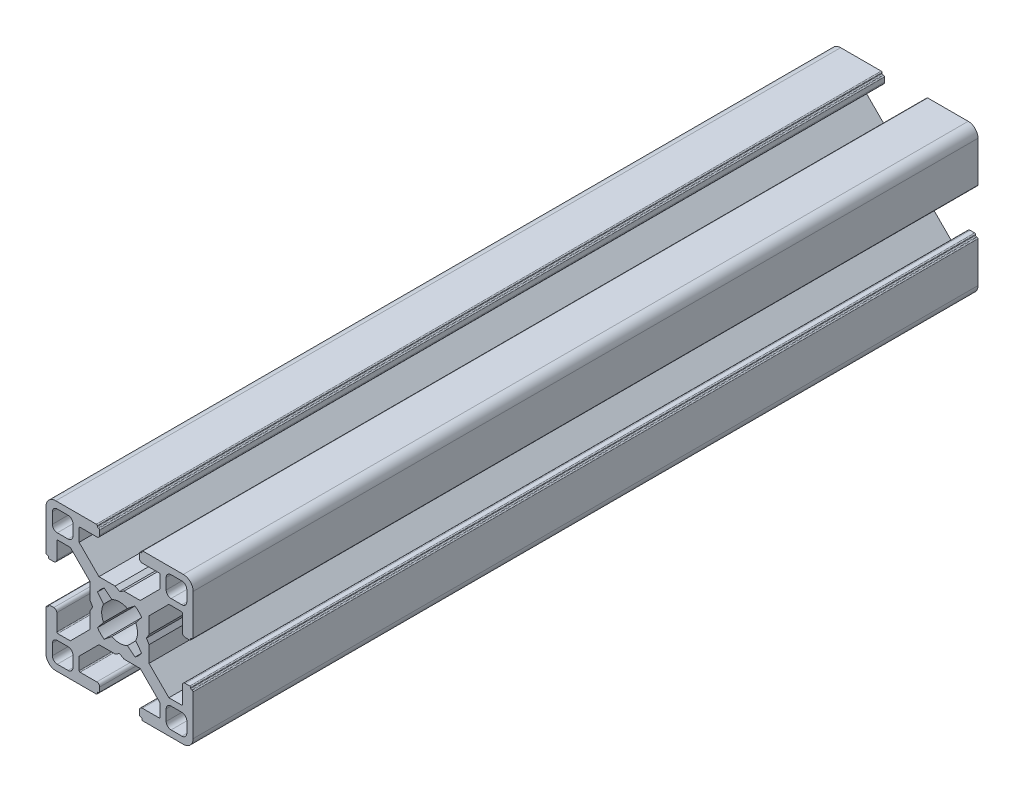
SolidWorks part; units mm, degrees
material "6061 Alloy"
ref_plane "Front" through (0, 0, 0) normal (0, 0, 1) x (1, 0, 0)
ref_plane "Top" through (0, 0, 0) normal (0, 1, 0) x (1, 0, 0)
ref_plane "Right" through (0, 0, 0) normal (1, 0, 0) x (0, 0, -1)
sketch "Sketch1" plane through (0, 0, 0) normal (0, 0, 1) x (1, 0, 0)
  line L0 (13.7, 12.7) -> (13.7, 10.5)
  line L1 (10.5, 9.5) -> (12.7, 9.5)
  line L2 (9.5, 12.7) -> (9.5, 10.5)
  line L3 (10.5, 13.7) -> (12.7, 13.7)
  line L4 (3.1359, 4.5184) -> (1.6001, 3.2806)
  line L5 (3.2806, 1.6001) -> (4.5053, 3.1547)
  line L6 (6.0045, 0.9) -> (5.4849, 0)
  line L7 (6.0045, 4.2045) -> (6.0045, 0.9)
  line L8 (0, -5.4849) -> (0.9, -6)
  line L9 (0.9, -6) -> (4.2045, -6)
  line L10 (4.2045, -6) -> (8.25, -10.05)
  line L11 (8.25, -10.05) -> (8.25, -12.6)
  line L12 (4.65, -12.8) -> (8.05, -12.8)
  line L13 (4.05, -14.3) -> (4.05, -13.4)
  line L14 (4.25, -14.5) -> (4.35, -14.5)
  line L15 (4.55, -14.8) -> (4.55, -14.7)
  line L16 (4.75, -15) -> (13, -15)
  line L17 (15, -13) -> (15, -4.75)
  line L18 (14.7, -4.55) -> (14.8, -4.55)
  line L19 (14.5, -4.35) -> (14.5, -4.25)
  line L20 (13.4, -4.05) -> (14.3, -4.05)
  line L21 (12.8, -8.05) -> (12.8, -4.65)
  line L22 (12.6, -8.25) -> (10.05, -8.25)
  line L23 (10.05, -8.25) -> (6.0045, -4.2045)
  line L24 (6.0045, -4.2045) -> (6.0045, -0.9)
  line L25 (6.0045, -0.9) -> (5.4849, 0)
  line L26 (10.05, 8.25) -> (6.0045, 4.2045)
  line L27 (12.6, 8.25) -> (10.05, 8.25)
  line L28 (12.8, 8.05) -> (12.8, 4.65)
  line L29 (13.4, 4.05) -> (14.3, 4.05)
  line L30 (14.5, 4.35) -> (14.5, 4.25)
  line L31 (14.7, 4.55) -> (14.8, 4.55)
  line L32 (15, 13) -> (15, 4.75)
  line L33 (4.75, 15) -> (13, 15)
  line L34 (4.55, 14.8) -> (4.55, 14.7)
  line L35 (4.25, 14.5) -> (4.35, 14.5)
  line L36 (4.05, 14.3) -> (4.05, 13.4)
  line L37 (4.65, 12.8) -> (8.05, 12.8)
  line L38 (8.25, 10.05) -> (8.25, 12.6)
  line L39 (4.2045, 6) -> (8.25, 10.05)
  line L40 (0.9, 6) -> (4.2045, 6)
  line L41 (0, 5.4849) -> (0.9, 6)
  line L42 (-13.7, -12.7) -> (-13.7, -10.5)
  line L43 (-10.5, -9.5) -> (-12.7, -9.5)
  line L44 (-9.5, -12.7) -> (-9.5, -10.5)
  line L45 (-10.5, -13.7) -> (-12.7, -13.7)
  line L46 (-3.1359, -4.5184) -> (-1.6001, -3.2806)
  line L47 (-3.2806, -1.6001) -> (-4.5053, -3.1547)
  line L48 (0, 5.4849) -> (-0.9, 6)
  line L49 (-0.9, 6) -> (-4.2045, 6)
  line L50 (-4.2045, 6) -> (-8.25, 10.05)
  line L51 (-8.25, 10.05) -> (-8.25, 12.6)
  line L52 (-4.65, 12.8) -> (-8.05, 12.8)
  line L53 (-4.05, 14.3) -> (-4.05, 13.4)
  line L54 (-4.25, 14.5) -> (-4.35, 14.5)
  line L55 (-4.55, 14.8) -> (-4.55, 14.7)
  line L56 (-4.75, 15) -> (-13, 15)
  line L57 (-15, 13) -> (-15, 4.75)
  line L58 (-14.7, 4.55) -> (-14.8, 4.55)
  line L59 (-14.5, 4.35) -> (-14.5, 4.25)
  line L60 (-13.4, 4.05) -> (-14.3, 4.05)
  line L61 (-12.8, 8.05) -> (-12.8, 4.65)
  line L62 (-12.6, 8.25) -> (-10.05, 8.25)
  line L63 (-10.05, 8.25) -> (-6.0045, 4.2045)
  line L64 (-6.0045, -0.9) -> (-5.4849, 0)
  line L65 (-6.0045, -4.2045) -> (-6.0045, -0.9)
  line L66 (-10.05, -8.25) -> (-6.0045, -4.2045)
  line L67 (-12.6, -8.25) -> (-10.05, -8.25)
  line L68 (-12.8, -8.05) -> (-12.8, -4.65)
  line L69 (-13.4, -4.05) -> (-14.3, -4.05)
  line L70 (-14.5, -4.35) -> (-14.5, -4.25)
  line L71 (-14.7, -4.55) -> (-14.8, -4.55)
  line L72 (-15, -13) -> (-15, -4.75)
  line L73 (-4.75, -15) -> (-13, -15)
  line L74 (-4.55, -14.8) -> (-4.55, -14.7)
  line L75 (-4.25, -14.5) -> (-4.35, -14.5)
  line L76 (-4.05, -14.3) -> (-4.05, -13.4)
  line L77 (3.2806, -1.6001) -> (4.5053, -3.1547)
  line L78 (3.1359, -4.5184) -> (1.6001, -3.2806)
  line L79 (-4.65, -12.8) -> (-8.05, -12.8)
  line L80 (-8.25, -10.05) -> (-8.25, -12.6)
  line L81 (-4.2045, -6) -> (-8.25, -10.05)
  line L82 (-0.9, -6) -> (-4.2045, -6)
  line L83 (0, -5.4849) -> (-0.9, -6)
  line L84 (10.5, -13.7) -> (12.7, -13.7)
  line L85 (9.5, -12.7) -> (9.5, -10.5)
  line L86 (10.5, -9.5) -> (12.7, -9.5)
  line L87 (13.7, -12.7) -> (13.7, -10.5)
  line L88 (-6.0045, 4.2045) -> (-6.0045, 0.9)
  line L89 (-6.0045, 0.9) -> (-5.4849, 0)
  line L90 (-3.2806, 1.6001) -> (-4.5053, 3.1547)
  line L91 (-3.1359, 4.5184) -> (-1.6001, 3.2806)
  line L92 (-10.5, 13.7) -> (-12.7, 13.7)
  line L93 (-9.5, 12.7) -> (-9.5, 10.5)
  line L94 (-10.5, 9.5) -> (-12.7, 9.5)
  line L95 (-13.7, 12.7) -> (-13.7, 10.5)
  line L96 (-23.4857, 0) -> (20.9308, 0) construction
  line L97 (0, 17.9563) -> (0, -17.361) construction
  arc A0 (13.7, 12.7) -> (12.7, 13.7) centre (12.7, 12.7) ccw
  arc A1 (12.7, 9.5) -> (13.7, 10.5) centre (12.7, 10.5) ccw
  arc A2 (9.5, 10.5) -> (10.5, 9.5) centre (10.5, 10.5) ccw
  arc A3 (10.5, 13.7) -> (9.5, 12.7) centre (10.5, 12.7) ccw
  arc A4 (1.6001, 3.2806) -> (-1.6001, 3.2806) centre (0, 0) ccw
  arc A5 (8.25, -12.6) -> (8.05, -12.8) centre (8.05, -12.6) cw
  arc A6 (4.65, -12.8) -> (4.05, -13.4) centre (4.65, -13.4) ccw
  arc A7 (4.05, -14.3) -> (4.25, -14.5) centre (4.25, -14.3) ccw
  arc A8 (4.35, -14.5) -> (4.55, -14.7) centre (4.35, -14.7) cw
  arc A9 (4.55, -14.8) -> (4.75, -15) centre (4.75, -14.8) ccw
  arc A10 (13, -15) -> (15, -13) centre (13, -13) ccw
  arc A11 (15, -4.75) -> (14.8, -4.55) centre (14.8, -4.75) ccw
  arc A12 (14.7, -4.55) -> (14.5, -4.35) centre (14.7, -4.35) cw
  arc A13 (14.5, -4.25) -> (14.3, -4.05) centre (14.3, -4.25) ccw
  arc A14 (13.4, -4.05) -> (12.8, -4.65) centre (13.4, -4.65) ccw
  arc A15 (12.8, -8.05) -> (12.6, -8.25) centre (12.6, -8.05) cw
  arc A16 (4.5053, 3.1547) -> (3.1359, 4.5184) centre (0, 0) ccw
  arc A17 (12.8, 8.05) -> (12.6, 8.25) centre (12.6, 8.05) ccw
  arc A18 (13.4, 4.05) -> (12.8, 4.65) centre (13.4, 4.65) cw
  arc A19 (14.5, 4.25) -> (14.3, 4.05) centre (14.3, 4.25) cw
  arc A20 (14.7, 4.55) -> (14.5, 4.35) centre (14.7, 4.35) ccw
  arc A21 (15, 4.75) -> (14.8, 4.55) centre (14.8, 4.75) cw
  arc A22 (13, 15) -> (15, 13) centre (13, 13) cw
  arc A23 (4.55, 14.8) -> (4.75, 15) centre (4.75, 14.8) cw
  arc A24 (4.35, 14.5) -> (4.55, 14.7) centre (4.35, 14.7) ccw
  arc A25 (4.05, 14.3) -> (4.25, 14.5) centre (4.25, 14.3) cw
  arc A26 (4.65, 12.8) -> (4.05, 13.4) centre (4.65, 13.4) cw
  arc A27 (8.25, 12.6) -> (8.05, 12.8) centre (8.05, 12.6) ccw
  arc A28 (-13.7, -12.7) -> (-12.7, -13.7) centre (-12.7, -12.7) ccw
  arc A29 (-12.7, -9.5) -> (-13.7, -10.5) centre (-12.7, -10.5) ccw
  arc A30 (-9.5, -10.5) -> (-10.5, -9.5) centre (-10.5, -10.5) ccw
  arc A31 (-10.5, -13.7) -> (-9.5, -12.7) centre (-10.5, -12.7) ccw
  arc A32 (-4.5053, -3.1547) -> (-3.1359, -4.5184) centre (0, 0) ccw
  arc A33 (-3.2806, 1.6001) -> (-3.2806, -1.6001) centre (0, 0) ccw
  arc A34 (-8.25, 12.6) -> (-8.05, 12.8) centre (-8.05, 12.6) cw
  arc A35 (-4.65, 12.8) -> (-4.05, 13.4) centre (-4.65, 13.4) ccw
  arc A36 (-4.05, 14.3) -> (-4.25, 14.5) centre (-4.25, 14.3) ccw
  arc A37 (-4.35, 14.5) -> (-4.55, 14.7) centre (-4.35, 14.7) cw
  arc A38 (-4.55, 14.8) -> (-4.75, 15) centre (-4.75, 14.8) ccw
  arc A39 (-13, 15) -> (-15, 13) centre (-13, 13) ccw
  arc A40 (-15, 4.75) -> (-14.8, 4.55) centre (-14.8, 4.75) ccw
  arc A41 (-14.7, 4.55) -> (-14.5, 4.35) centre (-14.7, 4.35) cw
  arc A42 (-14.5, 4.25) -> (-14.3, 4.05) centre (-14.3, 4.25) ccw
  arc A43 (-13.4, 4.05) -> (-12.8, 4.65) centre (-13.4, 4.65) ccw
  arc A44 (-12.8, 8.05) -> (-12.6, 8.25) centre (-12.6, 8.05) cw
  arc A45 (-4.5053, 3.1547) -> (-3.1359, 4.5184) centre (0, 0) cw
  arc A46 (-12.8, -8.05) -> (-12.6, -8.25) centre (-12.6, -8.05) ccw
  arc A47 (-13.4, -4.05) -> (-12.8, -4.65) centre (-13.4, -4.65) cw
  arc A48 (-14.5, -4.25) -> (-14.3, -4.05) centre (-14.3, -4.25) cw
  arc A49 (3.2806, 1.6001) -> (3.2806, -1.6001) centre (0, 0) cw
  arc A50 (4.5053, -3.1547) -> (3.1359, -4.5184) centre (0, 0) cw
  arc A51 (1.6001, -3.2806) -> (-1.6001, -3.2806) centre (0, 0) cw
  arc A52 (-14.7, -4.55) -> (-14.5, -4.35) centre (-14.7, -4.35) ccw
  arc A53 (-15, -4.75) -> (-14.8, -4.55) centre (-14.8, -4.75) cw
  arc A54 (-13, -15) -> (-15, -13) centre (-13, -13) cw
  arc A55 (-4.55, -14.8) -> (-4.75, -15) centre (-4.75, -14.8) cw
  arc A56 (10.5, -13.7) -> (9.5, -12.7) centre (10.5, -12.7) cw
  arc A57 (9.5, -10.5) -> (10.5, -9.5) centre (10.5, -10.5) cw
  arc A58 (12.7, -9.5) -> (13.7, -10.5) centre (12.7, -10.5) cw
  arc A59 (13.7, -12.7) -> (12.7, -13.7) centre (12.7, -12.7) cw
  arc A60 (-4.35, -14.5) -> (-4.55, -14.7) centre (-4.35, -14.7) ccw
  arc A61 (-4.05, -14.3) -> (-4.25, -14.5) centre (-4.25, -14.3) cw
  arc A62 (-4.65, -12.8) -> (-4.05, -13.4) centre (-4.65, -13.4) cw
  arc A63 (-8.25, -12.6) -> (-8.05, -12.8) centre (-8.05, -12.6) ccw
  arc A64 (-10.5, 13.7) -> (-9.5, 12.7) centre (-10.5, 12.7) cw
  arc A65 (-9.5, 10.5) -> (-10.5, 9.5) centre (-10.5, 10.5) cw
  arc A66 (-12.7, 9.5) -> (-13.7, 10.5) centre (-12.7, 10.5) cw
  arc A67 (-13.7, 12.7) -> (-12.7, 13.7) centre (-12.7, 12.7) cw
  point P81 (15, 15)
  point P82 (0, 15)
  point P203 (0, -15)
  point P204 (15, -15)
  point P206 (0, 0)
  point P207 (15, 0)
  point P219 (-15, 0)
  point P220 (-15, -15)
  point P221 (-15, 15)
extrude "Base-Extrude" add sketch "Sketch1" against normal blind 160
sketch "草图2" plane through (15, 0, 0) normal (1, 0, 0) x (0, 0, -1)
  line L0 (0, 15) -> (30, -15)
  line L1 (160, -15) -> (0, -15) construction
  line L2 (0, 4.75) -> (0, 13) construction
  line L3 (0, 15) -> (0, -15)
  line L4 (0, -15) -> (30, -15)
  line L5 (-13.0087, 11.9543) -> (-11.263, 12.8943)
  dimension "D1" = 45
